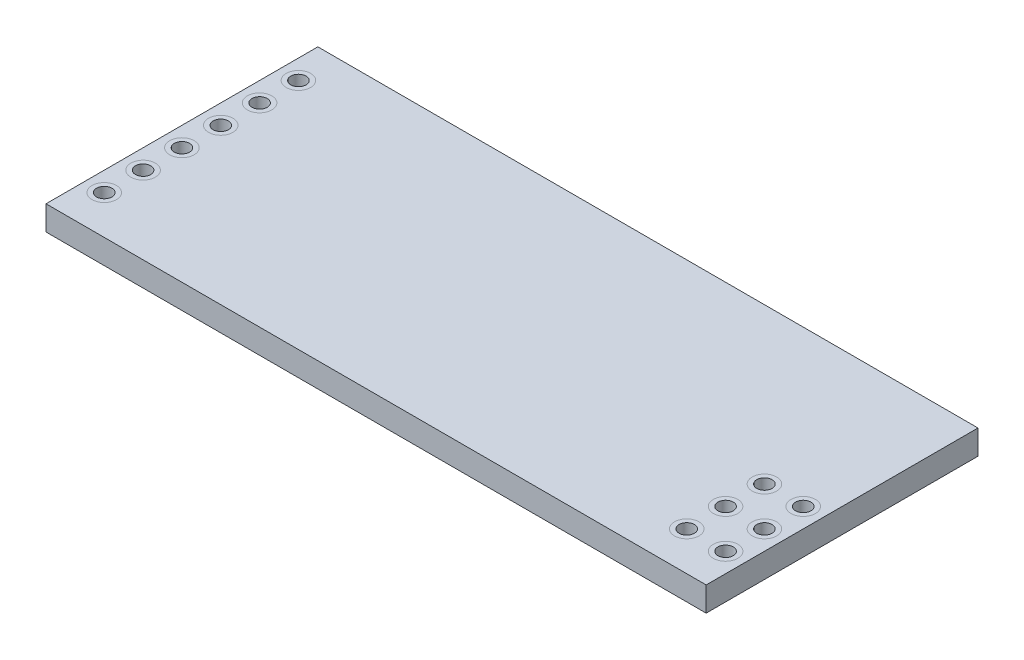
SolidWorks part; units mm, degrees
ref_plane "Front Plane" through (0, 0, 0) normal (0, 0, 1) x (1, 0, 0)
ref_plane "Top Plane" through (0, 0, 0) normal (0, 1, 0) x (1, 0, 0)
ref_plane "Right Plane" through (0, 0, 0) normal (1, 0, 0) x (0, 0, -1)
sketch "Sketch1" plane through (0, 0, 0) normal (0, 1, 0) x (1, 0, 0)
  line L0 (20.32, 8.89) -> (20.32, -8.89) construction
  line L1 (-21.59, 8.89) -> (21.59, 8.89)
  line L2 (-21.59, 8.89) -> (-21.59, -8.89)
  line L3 (-21.59, -8.89) -> (21.59, -8.89)
  line L4 (21.59, 8.89) -> (21.59, -8.89)
  line L5 (-21.59, 8.89) -> (21.59, -8.89) construction
  line L6 (-21.59, -8.89) -> (21.59, 8.89) construction
  line L7 (21.59, 0) -> (-21.59, 0) construction
  line L8 (-20.32, 8.89) -> (-20.32, -8.89) construction
  line L9 (17.78, 8.89) -> (17.78, -8.89) construction
  circle A0 centre (20.32, -6.35) radius 0.5
  circle A1 centre (-20.32, 3.81) radius 0.5
  circle A2 centre (-20.32, 1.27) radius 0.5
  circle A3 centre (-20.32, -1.27) radius 0.5
  circle A4 centre (-20.32, 6.35) radius 0.5
  circle A5 centre (-20.32, -3.81) radius 0.5
  circle A6 centre (-20.32, -6.35) radius 0.5
  circle A7 centre (17.78, -6.35) radius 0.5
  circle A8 centre (17.78, -3.81) radius 0.5
  circle A9 centre (17.78, -1.27) radius 0.5
  circle A10 centre (20.32, -3.81) radius 0.5
  circle A11 centre (20.32, -1.27) radius 0.5
  point P0 (0, 0)
  dimension "D4" = 1
  dimension "D1" = 17.78
  dimension "D2" = 43.18
  dimension "D3" = 1.27
  dimension "D5" = 1.27
  dimension "D6" = 6.35
  dimension "D8" = 2.54
  dimension "D9" = 2.54
  dimension "D11" = 2.54
  dimension "D12" = 2.54
  dimension "D7" = 6
  dimension "D13" = 2
  dimension "D10" = 3
extrude "Boss-Extrude1" add sketch "Sketch1" along normal blind 1.6
chamfer "Chamfer1" distance 0.3 angle 0.1 12 edges at (20.32, 1.6, 6.85) (17.78, 1.6, 6.85) (20.32, 1.6, 4.31) (17.78, 1.6, 4.31) (20.32, 1.6, 1.77) (17.78, 1.6, 1.77) (-20.32, 1.6, 6.85) (-20.32, 1.6, 4.31) (-20.32, 1.6, 1.77) (-20.32, 1.6, -0.77) (-20.32, 1.6, -3.31) (-20.32, 1.6, -5.85)
chamfer "Chamfer2" distance 0.3 angle 0.1 12 edges at (20.32, 0, 1.77) (17.78, 0, 1.77) (17.78, 0, 4.31) (20.32, 0, 4.31) (20.32, 0, 6.85) (17.78, 0, 6.85) (-20.32, 0, -5.85) (-20.32, 0, -3.31) (-20.32, 0, -0.77) (-20.32, 0, 1.77) (-20.32, 0, 4.31) (-20.32, 0, 6.85)
equation "\"holeDiameter\"=1"
equation "\"D4@Sketch1\"=\"holeDiameter\""
